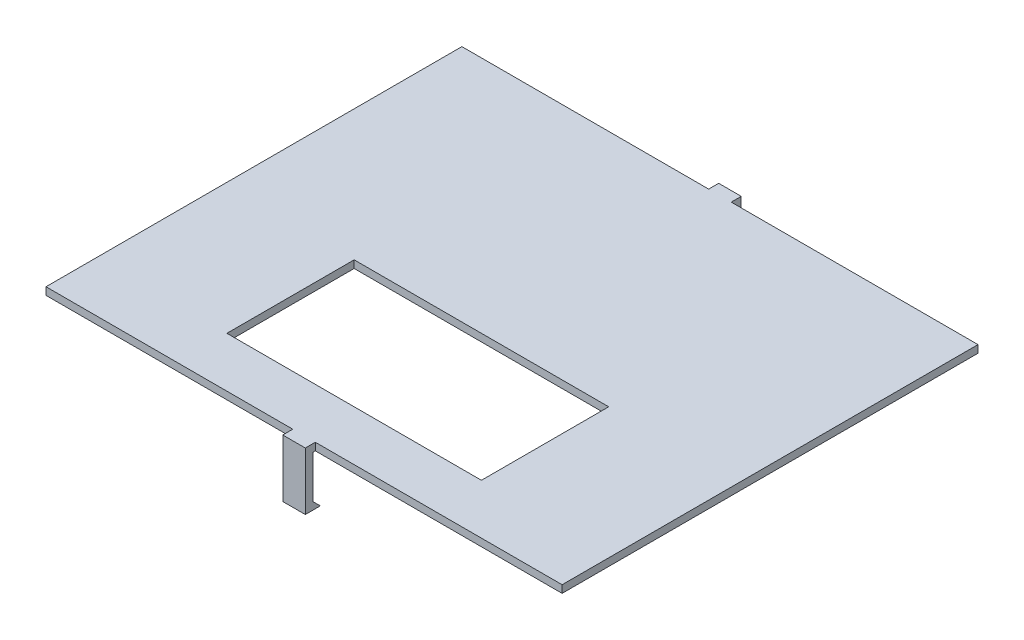
SolidWorks part; units mm, degrees
ref_plane "Front Plane" through (0, 0, 0) normal (0, 0, 1) x (1, 0, 0)
ref_plane "Top Plane" through (0, 0, 0) normal (0, 1, 0) x (1, 0, 0)
ref_plane "Right Plane" through (0, 0, 0) normal (1, 0, 0) x (0, 0, -1)
sketch "Sketch1" plane through (0, 0, 0) normal (0, 1, 0) x (1, 0, 0)
  line L1 (-33.2077, 29.4085) -> (69.7923, 29.4085)
  line L2 (-33.2077, 29.4085) -> (-33.2077, -53.5915)
  line L3 (-33.2077, -53.5915) -> (69.7923, -53.5915)
  line L4 (69.7923, 29.4085) -> (69.7923, -53.5915)
  dimension "D1" = 103
  dimension "D2" = 83
extrude "Boss-Extrude1" add sketch "Sketch1" along normal blind 1.5
ref_plane "Plane1" through (18.2923, 0, 0) normal (1, 0, 0) x (0, 0, -1)
sketch "Sketch2" plane through (18.2923, 0, 0) normal (1, 0, 0) x (0, 0, -1)
  line L2 (-53.5915, 1.5) -> (-55.5915, 1.5)
  line L3 (-55.5915, 1.5) -> (-55.5915, -10)
  line L4 (-55.5915, -10) -> (-52.5925, -10)
  line L5 (-52.5925, -10) -> (-54.0915, -8.5009)
  line L8 (-54.0915, -8.5009) -> (-54.0915, 0)
  line L9 (-12.0915, 0) -> (-12.0915, -22.2544) construction
  line L10 (-53.5915, 0) -> (29.4085, 0) construction
  line L11 (-54.0915, 0) -> (-53.5915, 0)
  line L12 (-53.5915, 0) -> (-53.5915, 1.5)
  line L13 (29.4085, 0) -> (29.4085, 1.5)
  line L14 (29.9085, 0) -> (29.4085, 0)
  line L15 (29.9085, -8.5009) -> (29.9085, 0)
  line L16 (28.4094, -10) -> (29.9085, -8.5009)
  line L17 (31.4085, -10) -> (28.4094, -10)
  line L18 (31.4085, 1.5) -> (31.4085, -10)
  line L19 (29.4085, 1.5) -> (31.4085, 1.5)
  dimension "D1" = 10
  dimension "D2" = 2.12
  dimension "D3" = 45
  dimension "D4" = 1.5
  dimension "D5" = 0.5
extrude "Boss-Extrude2" add sketch "Sketch2" along normal mid plane 4.5
sketch "Sketch3" plane through (0, 1.5, 0) normal (0, 1, 0) x (1, 0, 0)
  line L0 (18.2923, -55.6905) -> (18.2923, 31.4085) construction
  line L1 (-7.1077, -18.1915) -> (43.6923, -18.1915)
  line L2 (-7.1077, -18.1915) -> (-7.1077, -43.5915)
  line L3 (-7.1077, -43.5915) -> (43.6923, -43.5915)
  line L4 (43.6923, -18.1915) -> (43.6923, -43.5915)
  line L5 (18.2923, -11.8799) -> (18.2923, 11.8799) construction
  line L6 (20.5423, 31.4085) -> (16.0423, 31.4085) construction
  line L7 (-33.2077, -53.5915) -> (16.0423, -53.5915) construction
  line L8 (-33.2077, -12.0915) -> (69.7923, -12.0915) construction
  line L9 (-33.2077, 29.4085) -> (-33.2077, -53.5915) construction
  line L10 (69.7923, -53.5915) -> (69.7923, 29.4085) construction
  dimension "D1" = 25.4
  dimension "D2" = 50.8
  dimension "D3" = 35.4
  dimension "D4" = 25.4
extrude "Cut-Extrude1" cut sketch "Sketch3" against normal blind 1.5
